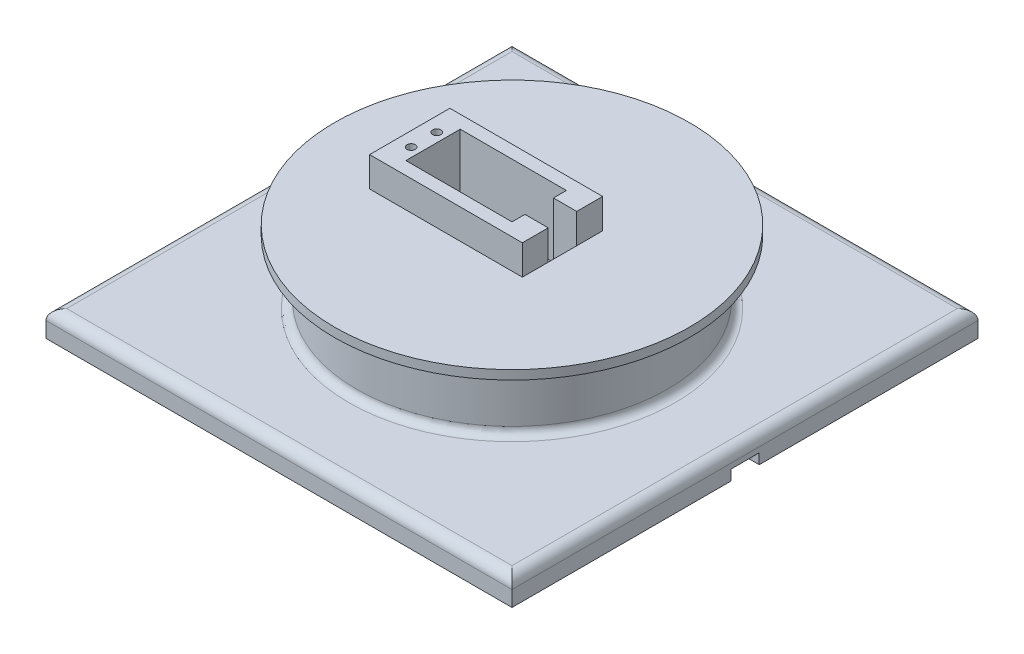
SolidWorks part; units mm, degrees
material "ABS PC"
ref_plane "Plan de face" through (0, 0, 0) normal (0, 0, 1) x (1, 0, 0)
ref_plane "Plan de dessus" through (0, 0, 0) normal (0, 1, 0) x (1, 0, 0)
ref_plane "Plan de droite" through (0, 0, 0) normal (1, 0, 0) x (0, 0, -1)
sketch "Esquisse1" plane through (0, 0, 0) normal (0, 1, 0) x (1, 0, 0)
  line L0 (0, 0) -> (0, 47.0919) construction
  line L1 (0, 0) -> (92.6466, 0) construction
  line L3 (-90, 90) -> (90, 90)
  line L4 (-90, 90) -> (-90, -90)
  line L5 (-90, -90) -> (90, -90)
  line L6 (90, 90) -> (90, -90)
  line L7 (-90, 90) -> (90, -90) construction
  line L8 (-90, -90) -> (90, 90) construction
  dimension "D1" = 180
extrude "Carré" add sketch "Esquisse1" along normal blind 10
sketch "Esquisse2" plane through (0, 10, 0) normal (0, 1, 0) x (1, 0, 0)
  line L0 (0, 0) -> (0, 98.5046) construction
  line L1 (0, 0) -> (154.8183, 0) construction
  circle A0 centre (0, 0) radius 60
  dimension "D1" = 120
extrude "Rond" add sketch "Esquisse2" along normal blind 28
fillet "Congé2" radius 4 4 edges at (0, 10, -90) (-90, 10, 0) (90, 10, 0) (0, 10, 90)
fillet "Congé8" radius 3 1 edges at (0, 10, 60)
sketch "Esquisse27" plane through (0, 38, 0) normal (0, 1, 0) x (1, 0, 0)
  line L0 (0, 0) -> (0, 60) construction
  circle A0 centre (0, 0) radius 60 construction
  circle A1 centre (0, 0) radius 68.5
  circle A2 centre (0, 0) radius 60 construction
  dimension "D1" = 8.5
extrude "Boss.-Extru.2" add sketch "Esquisse27" against normal blind 3.5
sketch "Esquisse4" [suppressed] plane through (0, 30, 0) normal (0, 1, 0) x (1, 0, 0)
  line L0 (0, 0) -> (0, 123.1569) construction
  line L1 (0, 0) -> (89.3073, 0) construction
  line L3 (-30.5, 10.5) -> (10.5, 10.5)
  line L4 (-30.5, 10.5) -> (-30.5, -10.5)
  line L5 (-30.5, -10.5) -> (10.5, -10.5)
  line L6 (10.5, 10.5) -> (10.5, -10.5)
  point P4 (0, 0)
  dimension "D1" = 41
  dimension "D2" = 30.5
  dimension "D3" = 21
extrude "Trou moteur" [suppressed] cut sketch "Esquisse4" against normal blind 6
fillet "Congé3" [suppressed] radius 2
sketch "Esquisse6" [suppressed] plane through (10.5, 0, 0) normal (-1, 0, 0) x (0, 0, 1)
  line L0 (0, 0) -> (0, 84.5069) construction
  line L1 (-12.5, 30) -> (12.5, 30) construction
  line L2 (-12.5, 30) -> (12.5, 30) construction
  line L4 (-3.5, 27) -> (3.5, 27)
  line L5 (-3.5, 27) -> (-3.5, 30)
  line L6 (-3.5, 30) -> (3.5, 30)
  line L7 (3.5, 27) -> (3.5, 30)
  line M7 (10.5, 28) -> (-10.5, 28)
  dimension "D1" = 3
  dimension "D2" = 7
extrude "Trachée Cable" [suppressed] cut sketch "Esquisse6" against normal through all contours L0 L7 L6 M7 | L4 L0 L2 L5
sketch "Esquisse7" [suppressed] plane through (0, 30, 0) normal (0, 1, 0) x (1, 0, 0)
  line L0 (0, 0) -> (-58.7915, 0) construction
  line L1 (-30.5, 12.5) -> (-30.5, -12.5)
  line L2 (-30.5, -12.5) -> (-37.5, -12.5)
  line L3 (-37.5, -12.5) -> (-37.5, 12.5)
  line L4 (-37.5, 12.5) -> (-30.5, 12.5)
  line L5 (-30.5, 12.5) -> (12.5, 12.5) construction
  line L6 (12.5, -12.5) -> (-30.5, -12.5) construction
  line L7 (-30.5, 12.5) -> (-30.5, -12.5) construction
  dimension "D1" = 7
extrude "Support arrière" [suppressed] add sketch "Esquisse7" along normal blind 20.5
sketch "Esquisse16" [suppressed] plane through (0, 24, 0) normal (0, 1, 0) x (1, 0, 0)
  line L0 (0, 0) -> (38.7391, 0) construction
  line L1 (0, 0) -> (0, 49.4872) construction
  line L3 (10.5, -10.5) -> (10.5, 10.5) construction
  line L4 (17.5, 12.5) -> (10.5, 12.5)
  line L5 (17.5, 12.5) -> (17.5, 3.5)
  line L6 (17.5, 3.5) -> (10.5, 3.5)
  line L7 (10.5, 12.5) -> (10.5, 3.5)
  line L8 (-37.5, -12.5) -> (-30.5, -12.5) construction
  line L9 (-30.5, 12.5) -> (12.5, 12.5) construction
  line L12 (10.5, -12.5) -> (10.5, -3.5)
  line L13 (17.5, -3.5) -> (10.5, -3.5)
  line L14 (17.5, -12.5) -> (17.5, -3.5)
  line L15 (17.5, -12.5) -> (10.5, -12.5)
  line L17 (59.7706, 3.5) -> (10.5, 3.5) construction
extrude "Support coté Cable" [suppressed] add sketch "Esquisse16" along normal blind 26.5
sketch "Esquisse17" [suppressed] plane through (0, 50.5, 0) normal (0, 1, 0) x (1, 0, 0)
  line L0 (0, 0) -> (21.9241, 0) construction
  line L1 (0, 0) -> (0, 24.8761) construction
  line L2 (-34, -12.5) -> (-34, 12.5) construction
  line L3 (-37.5, -12.5) -> (-30.5, -12.5) construction
  line L4 (-30.5, 12.5) -> (-37.5, 12.5) construction
  circle A0 centre (-34, -4.95) radius 2.5
  circle A2 centre (-34, 4.95) radius 2.5
  dimension "D2" = 5
  dimension "D1" = 9.9
hole_wizard "Dégagement M51" [suppressed] positions "Esquisse3D1" profile "Esquisse19" hole size "M5" standard "ISO"
sketch3d "Esquisse3D1" [suppressed]
  point P0 (-34, 50.5, 4.95)
  point P3 (-34, 50.5, -4.95)
sketch "Esquisse19" [suppressed] plane through (-34, 50.5, 4.95) normal (1, 0, 0) x (0, 0, 1)
  line L0 (0, 0) -> (0, 11.5923)
  line L1 (0, 11.5923) -> (2.65, 10)
  line L2 (2.65, 10) -> (2.65, 0)
  line L5 (2.65, 0) -> (0, 0)
  line L10 (0, 11.5923) -> (-2.65, 10) construction
  line L11 (0, -6.35) -> (0, 107.95) construction
  dimension "Diamètre du perçage" = 5.3
  dimension "Profondeur du perçage" = 10
  dimension "Angle de pointe" = 118
fillet "Congé4" [suppressed] radius 1
fillet "Congé10" [suppressed] radius 1
fillet "Congé11" [suppressed] radius 1
sketch "Esquisse20" plane through (0, 38, 0) normal (0, 1, 0) x (1, 0, 0)
  line L0 (0, 0) -> (45.2809, 0) construction
  line L1 (0, 0) -> (0, -47.1252) construction
  line L3 (10.5, 10.5) -> (-30.5, 10.5)
  line L4 (10.5, 10.5) -> (10.5, -10.5)
  line L5 (10.5, -10.5) -> (-30.5, -10.5)
  line L6 (-30.5, 10.5) -> (-30.5, -10.5)
  line L7 (10.5, 10.5) -> (-30.5, -10.5) construction
  line L8 (10.5, -10.5) -> (-30.5, 10.5) construction
  point P1 (-10, 0)
  dimension "D1" = 41
  dimension "D2" = 21
  dimension "D3" = 30.5
extrude "Enlèv. mat.-Extru.1" cut sketch "Esquisse20" against normal blind 15
sketch "Esquisse21" plane through (0, 23, 0) normal (0, 1, 0) x (1, 0, 0)
  line L0 (0, 0) -> (0, 39.703) construction
  line L1 (0, 0) -> (46.523, 0) construction
  line L2 (10.5, -10.5) -> (-30.5, 10.5) construction
  line L3 (-30.5, -10.5) -> (10.5, 10.5) construction
  line L5 (19.5, 15.5) -> (-39.5, 15.5)
  line L6 (19.5, 15.5) -> (19.5, -15.5)
  line L7 (19.5, -15.5) -> (-39.5, -15.5)
  line L8 (-39.5, 15.5) -> (-39.5, -15.5)
  line L9 (19.5, 15.5) -> (-39.5, -15.5) construction
  line L10 (19.5, -15.5) -> (-39.5, 15.5) construction
  line L13 (-30.5, -10.5) -> (10.5, -10.5) construction
  line L14 (-30.5, 10.5) -> (-30.5, -10.5) construction
  line L15 (10.5, 10.5) -> (-30.5, 10.5) construction
  line L16 (10.5, -10.5) -> (10.5, 10.5) construction
  line L25 (-30.5, -10.5) -> (10.5, -10.5)
  line L26 (-30.5, 10.5) -> (-30.5, -10.5)
  line L27 (10.5, 10.5) -> (-30.5, 10.5)
  line L28 (10.5, -10.5) -> (10.5, 10.5)
  point P7 (-10, 0)
  dimension "D1" = 9
  dimension "D2" = 5
extrude "Boss.-Extru.1" add sketch "Esquisse21" along normal blind 26.5
sketch "Esquisse22" plane through (0, 49.5, -36.5) normal (0, -1, 0) x (1, 0, 0)
  line L0 (0, 36.5) -> (21.9241, 36.5) construction
  line L1 (0, 36.5) -> (0, 24.8761) construction
  line L2 (-34, 31.55) -> (-34, 41.45) construction
  line L5 (-30.5, 26) -> (-30.5, 47) construction
  circle A0 centre (-34, 31.55) radius 2.5
  circle A2 centre (-34, 41.45) radius 2.5
  dimension "D2" = 5
  dimension "D1" = 9.9
  dimension "D3" = 3.5
hole_wizard "Dégagement M31" positions "Esquisse23" profile "Esquisse24" hole size "M3" standard "ISO"
sketch "Esquisse23" plane through (0, 49.5, 0) normal (0, 1, 0) x (1, 0, 0)
  point P0 (-34, 4.95)
  point P3 (-34, -4.95)
sketch "Esquisse24" plane through (-34, 49.5, -4.95) normal (1, 0, 0) x (0, 0, 1)
  line L0 (0, 0) -> (0, 4.9614)
  line L1 (0, 4.9614) -> (1.6, 4)
  line L2 (1.6, 4) -> (1.6, 0)
  line L5 (1.6, 0) -> (0, 0)
  line L10 (0, 4.9614) -> (-1.6, 4) construction
  line L11 (0, -6.35) -> (0, 107.95) construction
  dimension "Diamètre du perçage" = 3.2
  dimension "Profondeur du perçage" = 4
  dimension "Angle de pointe" = 118
sketch "Esquisse25" plane through (0, 49.5, 0) normal (0, 1, 0) x (1, 0, 0)
  line L0 (0, 0) -> (12.9452, 0) construction
  line L1 (0, 0) -> (0, 43.7499) construction
  line L2 (10.5, -10.5) -> (10.5, 10.5) construction
  line L3 (19.5, -15.5) -> (19.5, 15.5) construction
  line L4 (10.5, -5.5) -> (19.5, -5.5)
  line L5 (10.5, -5.5) -> (10.5, 5.5)
  line L6 (10.5, 5.5) -> (19.5, 5.5)
  line L7 (19.5, -5.5) -> (19.5, 5.5)
  point P14 (10.5, 0)
  dimension "D1" = 11
extrude "Enlèv. mat.-Extru.2" cut sketch "Esquisse25" against normal up to surface (49.5 mm away) up to face at (0, 0, 0)
sketch "Esquisse26" plane through (19.5, 0, 0) normal (-1, 0, 0) x (0, 0, 1)
  line L0 (0, 0) -> (0, 23.4493) construction
  line L1 (5.5, 0) -> (5.5, 38) construction
  line L2 (-5.5, 0) -> (-5.5, 38) construction
  line L4 (5.5, 0) -> (5.5, 4)
  line L5 (-5.5, 0) -> (-5.5, 4)
  line L6 (-5.5, 0) -> (5.5, 0)
  line L7 (-5.5, 4) -> (5.5, 4)
  dimension "D1" = 4
extrude "Enlèv. mat.-Extru.3" cut sketch "Esquisse26" against normal through all
